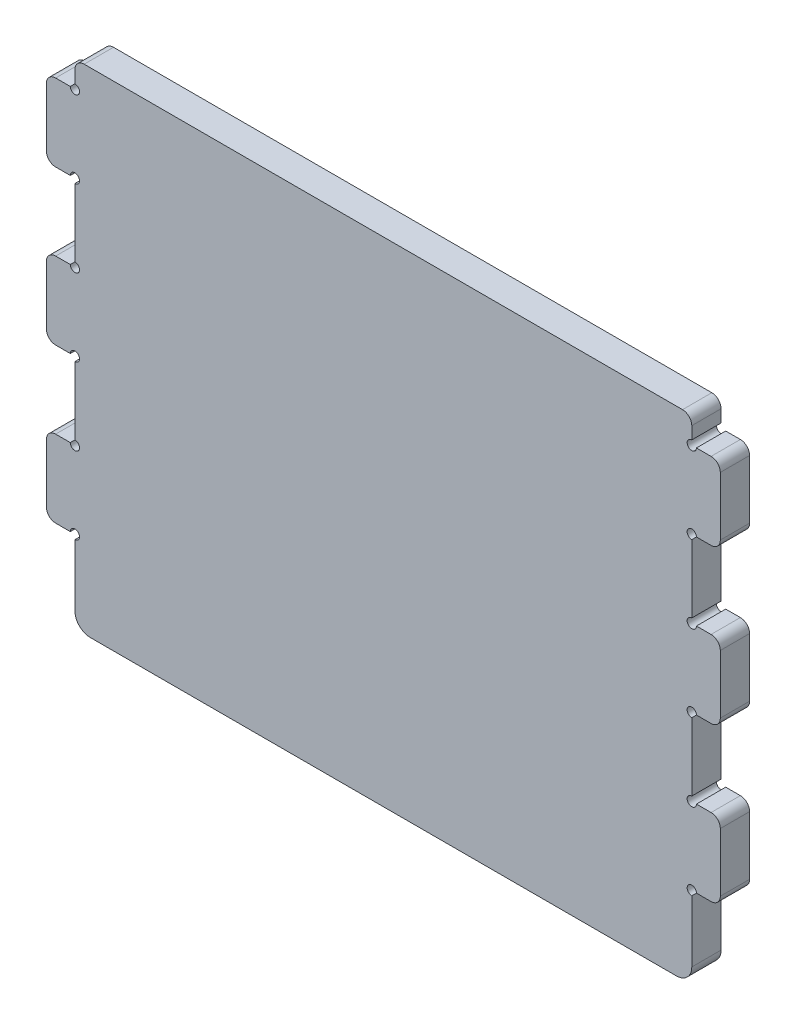
SolidWorks part; units mm, degrees
ref_plane "Front Plane" through (0, 0, 0) normal (0, 0, 1) x (1, 0, 0)
ref_plane "Top Plane" through (0, 0, 0) normal (0, 1, 0) x (1, 0, 0)
ref_plane "Right Plane" through (0, 0, 0) normal (1, 0, 0) x (0, 0, -1)
sketch "Sketch1" plane through (0, 0, 0) normal (0, 0, 1) x (1, 0, 0)
  line L0 (-212.5, 38) -> (-203, 38)
  line L1 (-200, -115) -> (-200, -155)
  line L2 (-200, 149) -> (-200, 141)
  line L3 (-190, -165) -> (190, -165)
  line L4 (200, 149) -> (200, 141)
  line L5 (-187.8788, 155) -> (200, -165) construction
  line L6 (-200, -165) -> (187.8788, 155) construction
  line L7 (-212.5, -62) -> (-203, -62)
  line L8 (-218.5, -68) -> (-218.5, -106)
  line L9 (-212.5, -112) -> (-203, -112)
  line L10 (-218.5, 32) -> (-218.5, -6)
  line L11 (-212.5, -12) -> (-203, -12)
  line L12 (-212.5, 138) -> (-203, 138)
  line L13 (-218.5, 132) -> (-218.5, 94)
  line L14 (-212.5, 88) -> (-203, 88)
  line L15 (0, 45.9462) -> (0, -39.4992) construction
  line L16 (212.5, 88) -> (203, 88)
  line L17 (218.5, 132) -> (218.5, 94)
  line L18 (212.5, 138) -> (203, 138)
  line L19 (212.5, -12) -> (203, -12)
  line L20 (218.5, 32) -> (218.5, -6)
  line L21 (212.5, -112) -> (203, -112)
  line L22 (218.5, -68) -> (218.5, -106)
  line L23 (212.5, -62) -> (203, -62)
  line L24 (212.5, 38) -> (203, 38)
  line L25 (-194, 155) -> (194, 155)
  line L26 (-200, 135) -> (-200, 91)
  line L27 (-200, 85) -> (-200, -59)
  line L28 (-200, -65) -> (-200, -109)
  line L29 (200, 135) -> (200, 91)
  line L30 (200, 85) -> (200, 41)
  line L31 (200, 35) -> (200, -9)
  line L32 (200, -15) -> (200, -59)
  line L33 (200, -65) -> (200, -109)
  line L34 (200, -115) -> (200, -155)
  arc A0 (-218.5, -106) -> (-212.5, -112) centre (-212.5, -106) ccw
  arc A1 (-212.5, -62) -> (-218.5, -68) centre (-212.5, -68) ccw
  arc A2 (-218.5, -6) -> (-212.5, -12) centre (-212.5, -6) ccw
  arc A3 (-212.5, 38) -> (-218.5, 32) centre (-212.5, 32) ccw
  arc A4 (-218.5, 94) -> (-212.5, 88) centre (-212.5, 94) ccw
  arc A5 (-212.5, 138) -> (-218.5, 132) centre (-212.5, 132) ccw
  arc A6 (212.5, 138) -> (218.5, 132) centre (212.5, 132) cw
  arc A7 (218.5, 94) -> (212.5, 88) centre (212.5, 94) cw
  arc A8 (212.5, 38) -> (218.5, 32) centre (212.5, 32) cw
  arc A9 (218.5, -6) -> (212.5, -12) centre (212.5, -6) cw
  arc A10 (212.5, -62) -> (218.5, -68) centre (212.5, -68) cw
  arc A11 (218.5, -106) -> (212.5, -112) centre (212.5, -106) cw
  arc A12 (-200, -155) -> (-190, -165) centre (-190, -155) ccw
  arc A13 (190, -165) -> (200, -155) centre (190, -155) ccw
  arc A14 (-200, -115) -> (-203, -112) centre (-200, -112) ccw
  arc A15 (-200, -115) -> (-203, -112) centre (-200, -112) ccw
  arc A16 (-203, -62) -> (-200, -59) centre (-200, -62) ccw
  arc A17 (-203, 38) -> (-200, 41) centre (-200, 38) ccw
  arc A18 (-200, -15) -> (-203, -12) centre (-200, -12) ccw
  arc A19 (-200, -15) -> (-203, -12) centre (-200, -12) ccw
  arc A20 (-203, 138) -> (-200, 141) centre (-200, 138) ccw
  arc A21 (-200, 85) -> (-203, 88) centre (-200, 88) ccw
  arc A22 (-200, 85) -> (-203, 88) centre (-200, 88) ccw
  arc A23 (200, -115) -> (203, -112) centre (200, -112) cw
  arc A24 (203, -62) -> (200, -59) centre (200, -62) cw
  arc A25 (200, -15) -> (203, -12) centre (200, -12) cw
  arc A26 (203, 38) -> (200, 41) centre (200, 38) cw
  arc A27 (200, 85) -> (203, 88) centre (200, 88) cw
  arc A28 (203, 138) -> (200, 141) centre (200, 138) cw
  arc A29 (194, 155) -> (200, 149) centre (194, 149) cw
  arc A30 (-200, 149) -> (-194, 155) centre (-194, 149) cw
  point P0 (0, 0)
  point P6 (-200, -87)
  point P13 (-218.5, -112)
  point P16 (-218.5, -62)
  point P19 (-200, 13)
  point P28 (-200, 113)
  point P61 (200, 113)
  point P62 (200, 13)
  point P63 (218.5, -62)
  point P64 (218.5, -112)
  point P65 (200, -87)
  dimension "D6" = 6
  dimension "D8" = 10
  dimension "D2" = 3
  dimension "D9" = 6
  dimension "D1" = 400
  dimension "D3" = 50
  dimension "D4" = 18.5
  dimension "D5" = 78
  dimension "D7" = 3
extrude "Boss-Extrude1" add sketch "Sketch1" along normal blind 19
